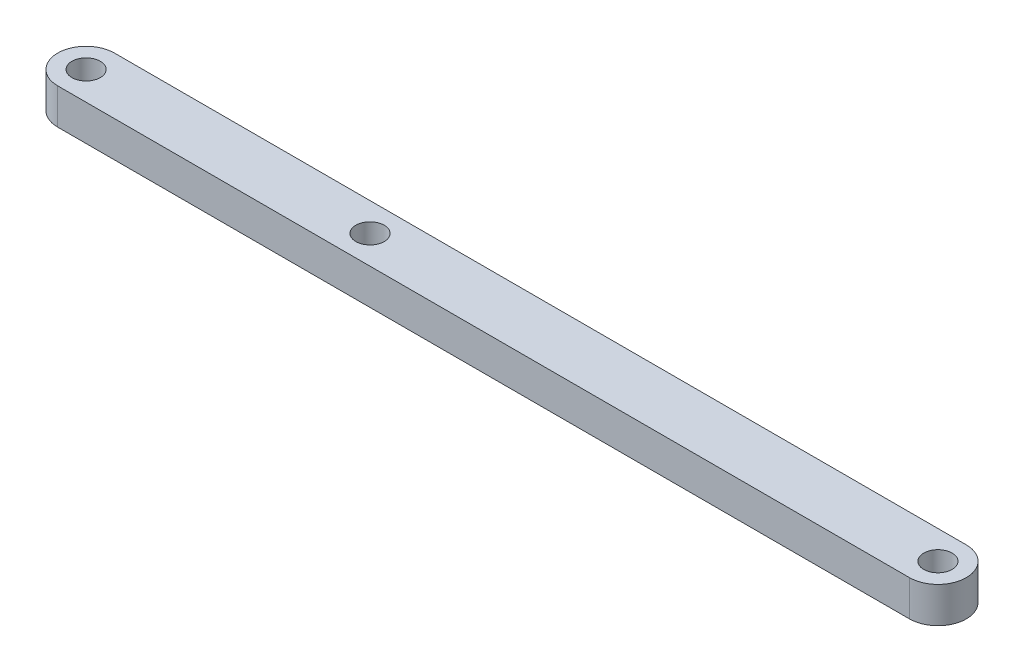
SolidWorks part; units mm, degrees
ref_plane "Front Plane" through (0, 0, 0) normal (0, 0, 1) x (1, 0, 0)
ref_plane "Top Plane" through (0, 0, 0) normal (0, 1, 0) x (1, 0, 0)
ref_plane "Right Plane" through (0, 0, 0) normal (1, 0, 0) x (0, 0, -1)
sketch "Sketch1" plane through (0, 0, 0) normal (0, 1, 0) x (1, 0, 0)
  line L0 (-95.25, 0) -> (0, 0) construction
  line L1 (-95.25, -2.54) -> (-19.05, -2.54)
  line L3 (-95.25, 2.54) -> (-19.05, 2.54)
  arc A0 (-95.25, 2.54) -> (-95.25, -2.54) centre (-95.25, 0) ccw
  arc A1 (-19.05, -2.54) -> (-19.05, 2.54) centre (-19.05, 0) ccw
  circle A2 centre (-95.25, 0) radius 1.27
  circle A3 centre (-19.05, 0) radius 1.27
  circle A4 centre (-69.85, 0) radius 1.27
  point P0 (0, 0)
  dimension "D3" = 25.4
  dimension "D4" = 2.54
  dimension "D1" = 76.2
  dimension "D2" = 5.08
extrude "Boss-Extrude1" add sketch "Sketch1" along normal blind 3.2004
